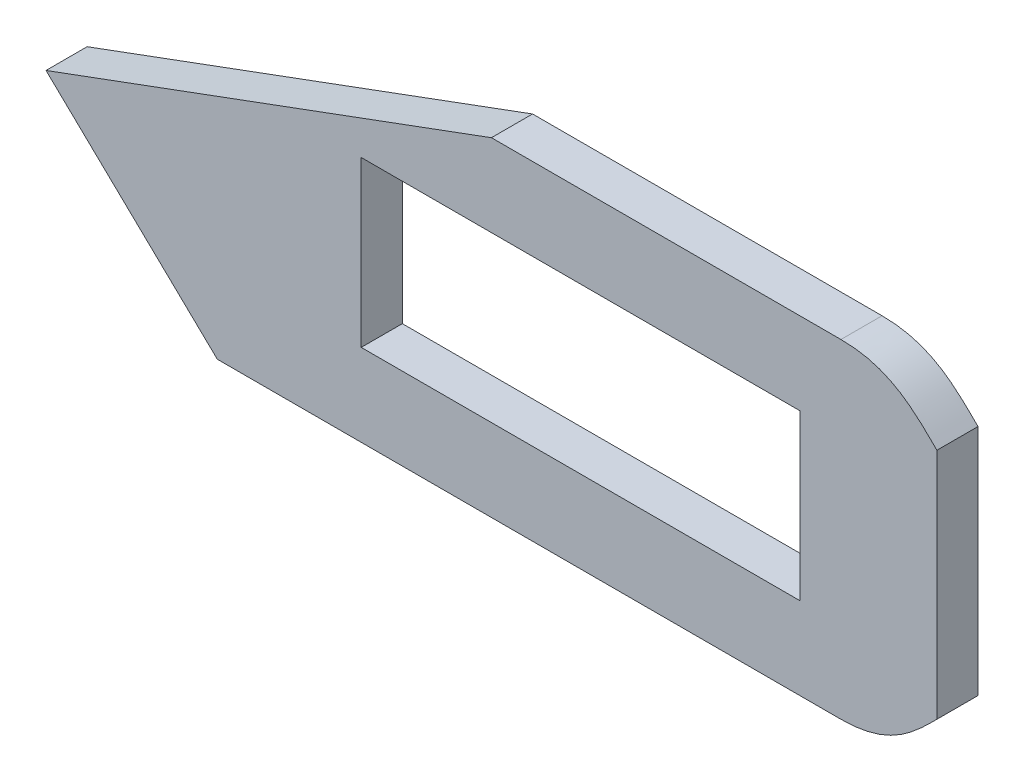
SolidWorks part; units mm, degrees
ref_plane "Plan de face" through (0, 0, 0) normal (0, 0, 1) x (1, 0, 0)
ref_plane "Plan de dessus" through (0, 0, 0) normal (0, 1, 0) x (1, 0, 0)
ref_plane "Plan de droite" through (0, 0, 0) normal (1, 0, 0) x (0, 0, -1)
sketch "Esquisse1" plane through (0, 0, 0) normal (0, 0, 1) x (1, 0, 0)
  line L0 (-34.4015, 0) -> (-21.9015, -12)
  line L1 (30.5985, -12) -> (-34.4015, -12)
  line L3 (30.5985, 12) -> (-34.4015, 12)
  line L4 (-34.4015, -12) -> (-34.4015, 12)
  line L5 (30.5985, -12) -> (-34.4015, 12) construction
  line L6 (30.5985, 12) -> (-34.4015, -12) construction
  line L7 (30.5985, 12) -> (30.5985, -12)
  line L20 (-34.4015, 0) -> (-1.9015, 12)
  line L21 (-11.4015, 6) -> (20.5985, 6)
  line L22 (-11.4015, 6) -> (-11.4015, -6)
  line L23 (-11.4015, -6) -> (20.5985, -6)
  line L33 (30.5985, 5) -> (37.5985, 5) construction
  line L34 (37.5985, 5) -> (37.5985, -5) construction
  line L35 (37.5985, -5) -> (30.5985, -5) construction
  line L36 (23.5985, 12) -> (30.5985, 12) construction
  line L37 (30.5985, 12) -> (30.5985, 5) construction
  line L38 (30.5985, 5) -> (37.5985, 5) construction
  line L39 (23.5985, -12) -> (30.5985, -12) construction
  line L40 (30.5985, -12) -> (30.5985, -5) construction
  line L41 (30.5985, -5) -> (37.5985, -5) construction
  line L42 (20.5985, 6) -> (20.5985, -6)
  spline S0 degree 3 poles (23.5985, 12) (30.5985, 12) (30.5985, 5) (37.5985, 5) knots 0 0 0 0 1 1 1 1
  spline S1 degree 3 poles (23.5985, -12) (30.5985, -12) (30.5985, -5) (37.5985, -5) knots 0 0 0 0 1 1 1 1
  point P8 (14.2956, 0.3737)
  dimension "D1" = 24
  dimension "D2" = 65
  dimension "D3" = 12
  dimension "D4" = 10
  dimension "D7" = 6
  dimension "D9" = 32
  dimension "D13" = 7
  dimension "D14" = 7
  dimension "D15" = 7
  dimension "D16" = 7
extrude "Boss.-Extru.1" add sketch "Esquisse1" along normal blind 3
